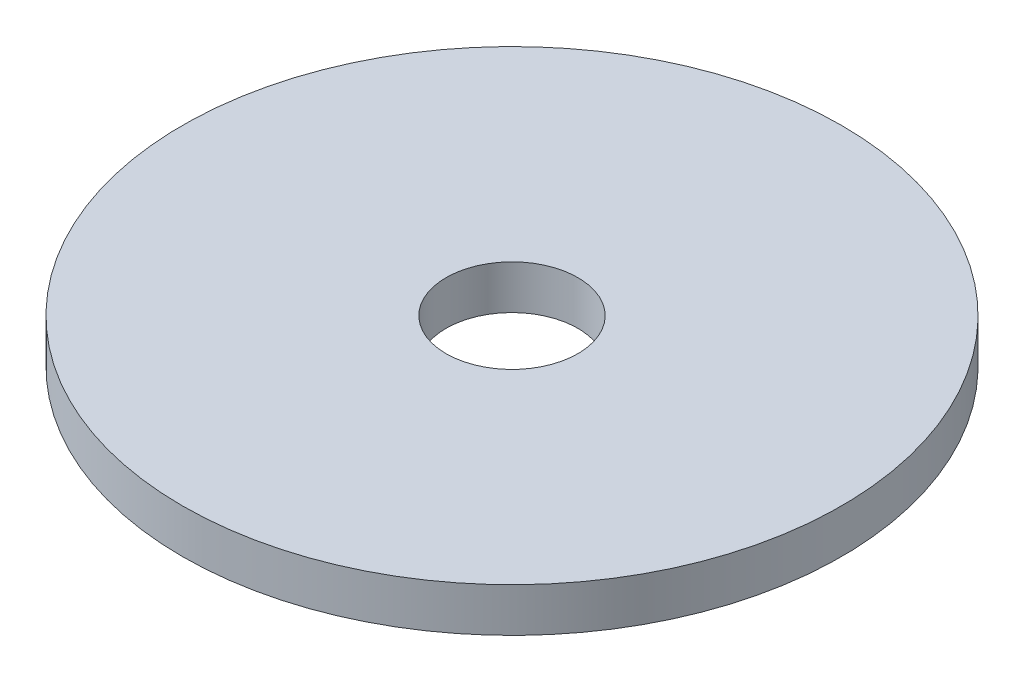
SolidWorks part; units mm, degrees
ref_plane "Front Plane" through (0, 0, 0) normal (0, 0, 1) x (1, 0, 0)
ref_plane "Top Plane" through (0, 0, 0) normal (0, 1, 0) x (1, 0, 0)
ref_plane "Right Plane" through (0, 0, 0) normal (1, 0, 0) x (0, 0, -1)
sketch "Sketch1" plane through (0, 0, 0) normal (0, 1, 0) x (1, 0, 0)
  circle A0 centre (0, 0) radius 1.5
  circle A1 centre (0, 0) radius 7.5
  dimension "D1" = 3
  dimension "D2" = 15
extrude "Boss-Extrude1" add sketch "Sketch1" along normal blind 1
